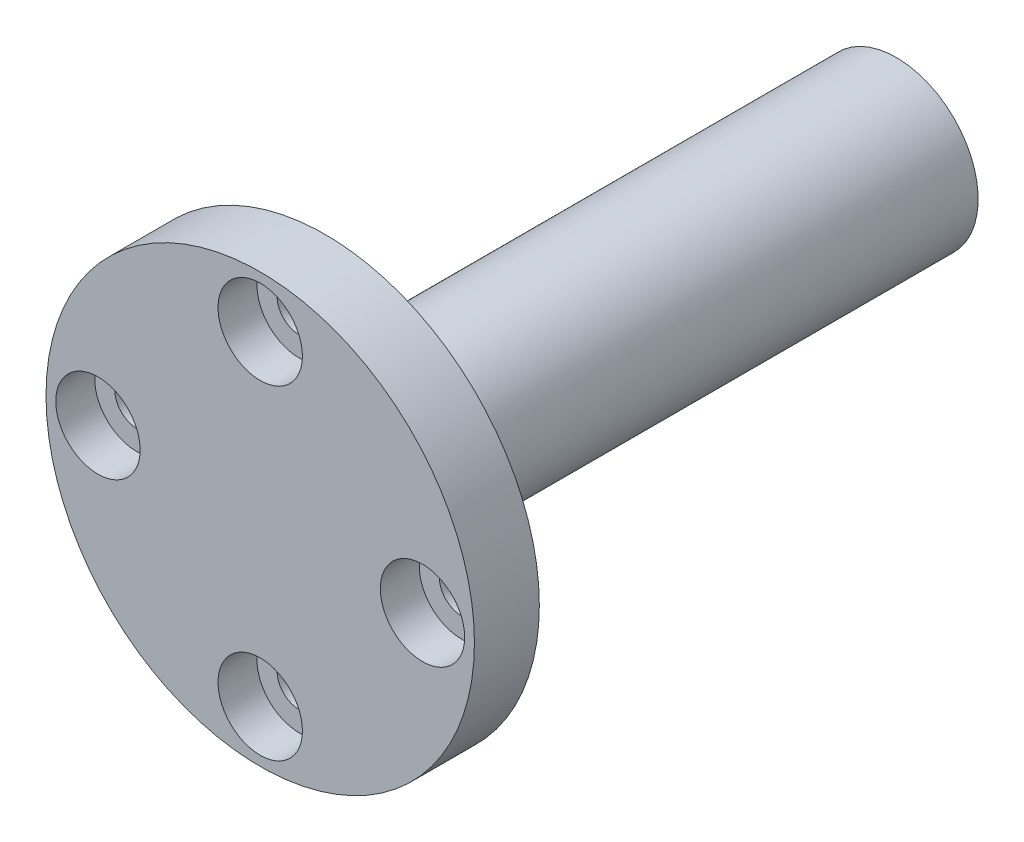
SolidWorks part; units mm, degrees
material "3.1355 (EN-AW 2024)"
ref_plane "Front" through (0, 0, 0) normal (0, 0, 1) x (1, 0, 0)
ref_plane "Top" through (0, 0, 0) normal (0, 1, 0) x (1, 0, 0)
ref_plane "Right" through (0, 0, 0) normal (1, 0, 0) x (0, 0, -1)
sketch "Эскиз2" plane through (0, 0, 0) normal (1, 0, 0) x (0, 0, -1)
  line L0 (0, 0) -> (0, 16.5)
  line L1 (0, 16.5) -> (5, 16.5)
  line L2 (5, 16.5) -> (5, 6.3)
  line L3 (5, 6.3) -> (49, 6.3)
  line L4 (49, 6.3) -> (49, 0)
  line L5 (49, 0) -> (0, 0)
  dimension "D1" = 16.5
  dimension "D2" = 5
  dimension "D3" = 6.3
  dimension "D4" = 44
  dimension "D5" = 49
revolve "Повернуть1" add sketch "Эскиз2" angle 360 about L5
sketch "Эскиз3" plane through (0, 0, 0) normal (0, 0, 1) x (1, 0, 0)
  circle A0 centre (0, 0) radius 12.5 construction
  point P3 (0, 12.5)
  point P7 (12.5, 0)
  point P8 (0, -12.5)
  point P9 (-12.5, 0)
  point P10 (0, 0)
  dimension "D1" = 25
  dimension "D2" = 4
hole_wizard "Цековка для винта с внутренним шестигранником M31" positions "Эскиз5" profile "Эскиз4" counterbore size "M3" standard "Ansi Metric" end condition through all
sketch "Эскиз5" plane through (0, 0, 0) normal (0, 0, 1) x (1, 0, 0)
  point P0 (-12.5, 0)
  point P3 (0, 12.5)
  point P6 (12.5, 0)
  point P9 (0, -12.5)
sketch "Эскиз4" plane through (-12.5, 0, 0) normal (1, 0, 0) x (0, -1, 0)
  line L0 (0, 0) -> (0, 49)
  line L1 (0, 49) -> (1.7, 49)
  line L3 (1.7, 49) -> (1.7, 3)
  line L4 (1.7, 3) -> (3.25, 3)
  line L5 (3.25, 3) -> (3.25, 0)
  line L7 (3.25, 0) -> (0, 0)
  line L11 (0, -6.35) -> (0, 107.95) construction
  dimension "Диаметр сквозного отверстия" = 3.4
  dimension "Глубина сквозного отверстия" = 49
  dimension "Диаметр цековки" = 6.5
  dimension "Глубина цековки" = 3
